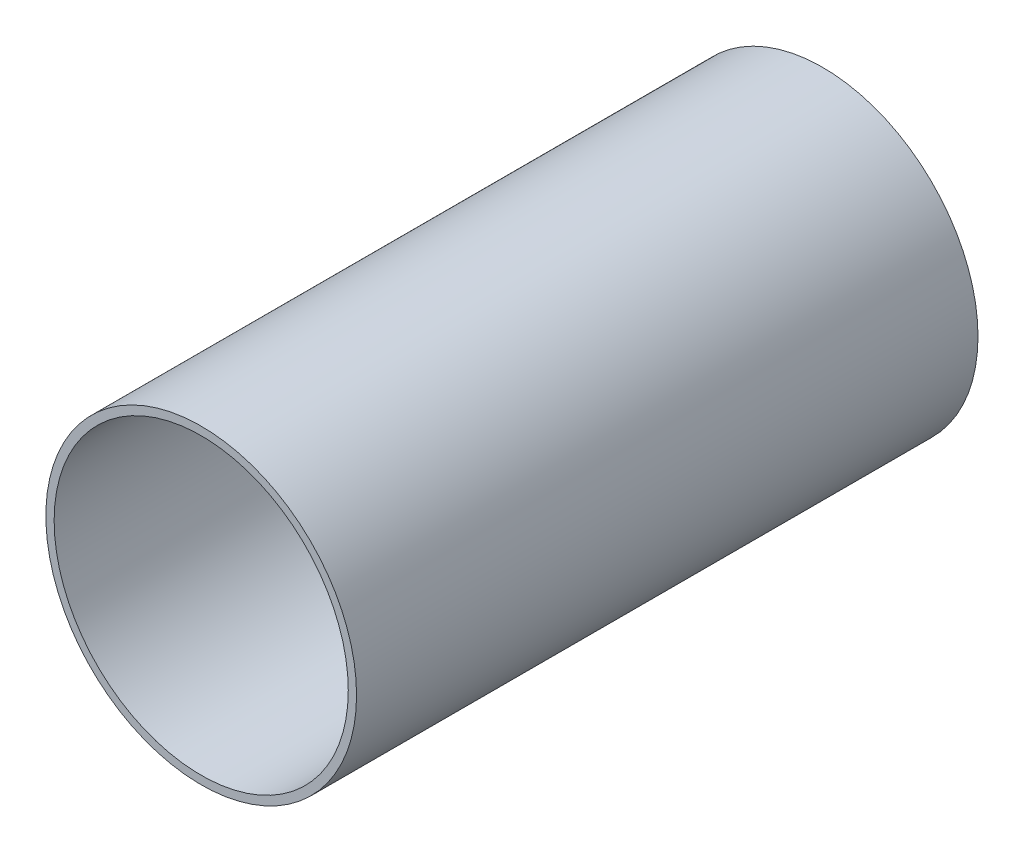
SolidWorks part; units mm, degrees
ref_plane "Front Plane" through (0, 0, 0) normal (0, 0, 1) x (1, 0, 0)
ref_plane "Top Plane" through (0, 0, 0) normal (0, 1, 0) x (1, 0, 0)
ref_plane "Right Plane" through (0, 0, 0) normal (1, 0, 0) x (0, 0, -1)
sketch "Sketch1" plane through (0, 0, 0) normal (0, 0, 1) x (1, 0, 0)
  circle A0 centre (-54.7807, 32.3957) radius 37.5
  circle A1 centre (-54.7807, 32.3957) radius 35.5
  dimension "D1" = 71
  dimension "D2" = 75
extrude "Boss-Extrude1" add sketch "Sketch1" along normal blind 150
